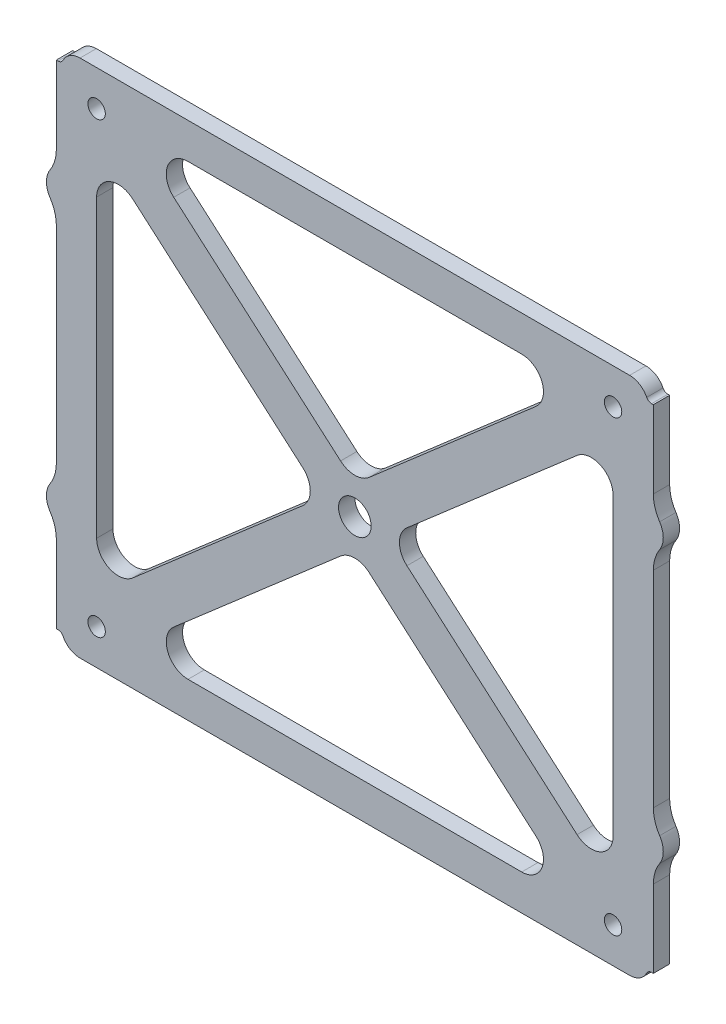
SolidWorks part; units mm, degrees
material "Thornel Mat VMA"
ref_plane "Front Plane" through (0, 0, 0) normal (0, 0, 1) x (1, 0, 0)
ref_plane "Top Plane" through (0, 0, 0) normal (0, 1, 0) x (1, 0, 0)
ref_plane "Right Plane" through (0, 0, 0) normal (1, 0, 0) x (0, 0, -1)
sketch "Sketch1" plane through (0, 0, 0) normal (0, 0, 1) x (-1, 0, 0)
  line L36 (-54.9091, 18.9246) -> (-54.9091, -18.9246)
  line L37 (-54.9091, -31.0754) -> (-54.9091, -45.3)
  line L38 (-54.9091, -45.3) -> (-54.5811, -45.3)
  line L39 (-50.55, -47.8) -> (50.55, -47.8)
  line L40 (54.5811, -45.3) -> (54.9091, -45.3)
  line L41 (54.9091, -45.3) -> (54.9091, -31.0754)
  line L42 (54.9091, -18.9246) -> (54.9091, 18.9246)
  line L43 (54.9091, 31.0754) -> (54.9091, 45.3)
  line L44 (54.9091, 45.3) -> (54.5811, 45.3)
  line L45 (50.55, 47.8) -> (-50.55, 47.8)
  line L46 (-54.5811, 45.3) -> (-54.9091, 45.3)
  line L47 (-54.9091, 45.3) -> (-54.9091, 31.0754)
  arc A20 (-56.0678, 27.218) -> (-56.0678, 22.782) centre (-52.7091, 25) ccw
  circle A24 centre (-47.5, 41.25) radius 1.6
  circle A33 centre (-47.5, -41.25) radius 1.6
  circle A36 centre (47.5, -41.25) radius 1.6
  arc A60 (-56.0678, -22.782) -> (-54.9091, -18.9246) centre (-61.9091, -18.9246) ccw
  arc A61 (-56.0678, -22.782) -> (-56.0678, -27.218) centre (-52.7091, -25) ccw
  arc A62 (-54.9091, -31.0754) -> (-56.0678, -27.218) centre (-61.9091, -31.0754) ccw
  arc A63 (-53.6853, -45.8556) -> (-54.5811, -45.3) centre (-54.5811, -46.3) ccw
  arc A64 (-53.6853, -45.8556) -> (-50.55, -47.8) centre (-50.55, -44.3) ccw
  arc A65 (50.55, -47.8) -> (53.6853, -45.8556) centre (50.55, -44.3) ccw
  arc A66 (54.5811, -45.3) -> (53.6853, -45.8556) centre (54.5811, -46.3) ccw
  arc A67 (56.0678, -27.218) -> (54.9091, -31.0754) centre (61.9091, -31.0754) ccw
  arc A68 (56.0678, -27.218) -> (56.0678, -22.782) centre (52.7091, -25) ccw
  arc A69 (54.9091, -18.9246) -> (56.0678, -22.782) centre (61.9091, -18.9246) ccw
  arc A70 (56.0678, 22.782) -> (54.9091, 18.9246) centre (61.9091, 18.9246) ccw
  arc A71 (56.0678, 22.782) -> (56.0678, 27.218) centre (52.7091, 25) ccw
  arc A72 (54.9091, 31.0754) -> (56.0678, 27.218) centre (61.9091, 31.0754) ccw
  arc A73 (53.6853, 45.8556) -> (54.5811, 45.3) centre (54.5811, 46.3) ccw
  arc A74 (53.6853, 45.8556) -> (50.55, 47.8) centre (50.55, 44.3) ccw
  arc A75 (-50.55, 47.8) -> (-53.6853, 45.8556) centre (-50.55, 44.3) ccw
  arc A76 (-54.5811, 45.3) -> (-53.6853, 45.8556) centre (-54.5811, 46.3) ccw
  arc A77 (-56.0678, 27.218) -> (-54.9091, 31.0754) centre (-61.9091, 31.0754) ccw
  arc A78 (-56.0678, 27.218) -> (-56.0678, 22.782) centre (-52.7091, 25) ccw
  arc A79 (-54.9091, 18.9246) -> (-56.0678, 22.782) centre (-61.9091, 18.9246) ccw
  circle A85 centre (47.5, 41.25) radius 1.6
  dimension "D1" = 3.2
  dimension "D3" = 3.2
  dimension "D4" = 3.2
  dimension "D5" = 3.2
  dimension "D2" = 0
extrude "Boss-Extrude1" add sketch "Sketch1" along normal blind 3
sketch "Sketch2" plane through (0, 0, 3) normal (0, 0, 1) x (1, 0, 0)
  line L2 (40.8773, -30.2009) -> (9.5782, -3.0201)
  line L3 (-33.3157, -34.2299) -> (-2.6227, -7.5754)
  line L4 (33.3157, -34.2299) -> (2.6227, -7.5754)
  line L5 (-40.8773, -30.2009) -> (-9.5782, -3.0201)
  line L6 (-47.5, -27.1808) -> (-47.5, 27.1808)
  line L7 (-30.693, 41.25) -> (30.693, 41.25)
  line L8 (47.5, 27.1808) -> (47.5, -27.1808)
  line L9 (-30.693, -41.25) -> (30.693, -41.25)
  line L13 (2.6227, 7.5754) -> (33.3157, 34.2299)
  line L16 (-9.5782, 3.0201) -> (-40.8773, 30.2009)
  line L17 (9.5782, 3.0201) -> (40.8773, 30.2009)
  line L18 (-2.6227, 7.5754) -> (-33.3157, 34.2299)
  arc A9 (-47.5, -27.1808) -> (-40.8773, -30.2009) centre (-43.5, -27.1808) ccw
  arc A10 (-33.3157, -34.2299) -> (-30.693, -41.25) centre (-30.693, -37.25) ccw
  arc A11 (33.3157, -34.2299) -> (30.693, -41.25) centre (30.693, -37.25) cw
  arc A12 (40.8773, -30.2009) -> (47.5, -27.1808) centre (43.5, -27.1808) ccw
  arc A13 (-2.6227, -7.5754) -> (2.6227, -7.5754) centre (0, -10.5956) cw
  arc A14 (9.5782, 3.0201) -> (9.5782, -3.0201) centre (12.2009, 0) ccw
  arc A15 (47.5, 27.1808) -> (40.8773, 30.2009) centre (43.5, 27.1808) ccw
  arc A16 (30.693, 41.25) -> (33.3157, 34.2299) centre (30.693, 37.25) cw
  arc A17 (-2.6227, 7.5754) -> (2.6227, 7.5754) centre (0, 10.5956) ccw
  arc A18 (-33.3157, 34.2299) -> (-30.693, 41.25) centre (-30.693, 37.25) cw
  arc A19 (-40.8773, 30.2009) -> (-47.5, 27.1808) centre (-43.5, 27.1808) ccw
  arc A20 (-9.5782, 3.0201) -> (-9.5782, -3.0201) centre (-12.2009, 0) cw
  point P33 (0, 5.2978)
  dimension "D1" = 4
extrude "Cut-Extrude1" cut sketch "Sketch2" against normal through all both and the other way through all
sketch "Sketch4" plane through (0, 0, 3) normal (0, 0, 1) x (1, 0, 0)
  circle A3 centre (0, 0) radius 3
extrude "Cut-Extrude2" cut sketch "Sketch4" against normal through all both and the other way through all
